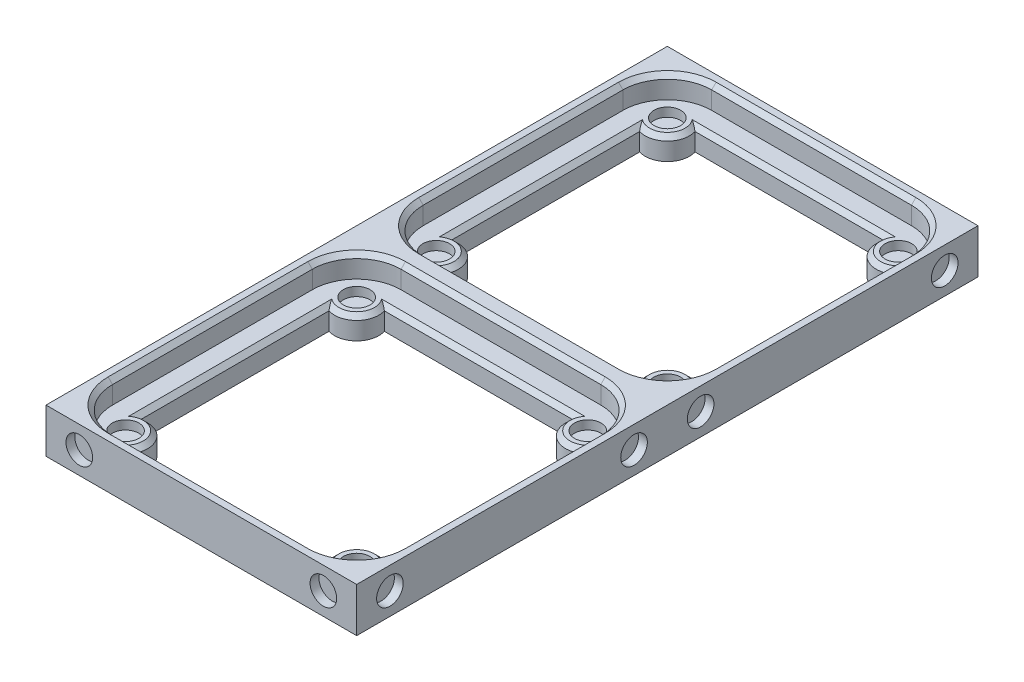
SolidWorks part; units mm, degrees
ref_plane "Front Plane" through (0, 0, 0) normal (0, 0, 1) x (1, 0, 0)
ref_plane "Top Plane" through (0, 0, 0) normal (0, 1, 0) x (1, 0, 0)
ref_plane "Right Plane" through (0, 0, 0) normal (1, 0, 0) x (0, 0, -1)
sketch "Sketch1" plane through (0, 0, 0) normal (0, 1, 0) x (1, 0, 0)
  line L1 (0, 0) -> (70, 0)
  line L2 (0, 0) -> (0, 70)
  line L3 (0, 70) -> (70, 70)
  line L4 (70, 0) -> (70, 70)
  dimension "D1" = 70
  dimension "D2" = 70
extrude "Boss-Extrude2" add sketch "Sketch1" along normal blind 7
sketch "Sketch3" plane through (0, 7, 0) normal (0, 1, 0) x (1, 0, 0)
  line L8 (2.5, 67.5) -> (2.5, 2.5)
  line L9 (2.5, 2.5) -> (67.5, 2.5)
  line L10 (67.5, 2.5) -> (67.5, 67.5)
  line L11 (67.5, 67.5) -> (2.5, 67.5)
  line L12 (2.5, 57.5) -> (2.5, 12.5)
  line L13 (12.5, 2.5) -> (57.5, 2.5)
  line L14 (67.5, 12.5) -> (67.5, 57.5)
  line L15 (57.5, 67.5) -> (12.5, 67.5)
  arc A0 (2.5, 12.5) -> (12.5, 2.5) centre (12.5, 12.5) ccw
  arc A1 (57.5, 2.5) -> (67.5, 12.5) centre (57.5, 12.5) ccw
  arc A2 (67.5, 57.5) -> (57.5, 67.5) centre (57.5, 57.5) ccw
  arc A3 (2.5, 57.5) -> (12.5, 67.5) centre (12.5, 57.5) cw
  dimension "D2" = 10
  dimension "D1" = 2.5
extrude "Cut-Extrude1" cut sketch "Sketch3" against normal blind 5
sketch "Sketch9" plane through (0, 0, 0) normal (0, -1, 0) x (1, 0, 0)
  line L1 (0, -70) -> (70, -70)
  line L2 (0, -70) -> (0, 0)
  line L3 (0, 0) -> (70, 0)
  line L4 (70, -70) -> (70, 0)
extrude "Boss-Extrude3" add sketch "Sketch9" along normal blind 5
sketch "Sketch20" plane through (0, 2, 0) normal (0, 1, 0) x (1, 0, 0)
  line L0 (35, 35) -> (8.9645, 61.0355) construction
  line L19 (12.5, 7.5) -> (57.5, 7.5)
  line L20 (62.5, 12.5) -> (62.5, 57.5)
  line L21 (57.5, 62.5) -> (12.5, 62.5)
  line L22 (7.5, 57.5) -> (7.5, 12.5)
  line L23 (13.7452, 7.5) -> (56.2548, 7.5)
  line L24 (62.5, 13.7452) -> (62.5, 56.2548)
  line L25 (56.2548, 62.5) -> (13.7452, 62.5)
  line L26 (7.5, 56.2548) -> (7.5, 13.7452)
  arc A0 (56.2548, 62.5) -> (62.5, 56.2548) centre (61.0355, 61.0355) ccw
  arc A1 (62.5, 13.7452) -> (56.2548, 7.5) centre (61.0355, 8.9645) ccw
  arc A2 (13.7452, 7.5) -> (7.5, 13.7452) centre (8.9645, 8.9645) ccw
  circle A4 centre (8.9645, 61.0355) radius 3
  circle A5 centre (8.9645, 8.9645) radius 3
  circle A6 centre (61.0355, 8.9645) radius 3
  circle A7 centre (61.0355, 61.0355) radius 3
  arc A21 (7.5, 56.2548) -> (13.7452, 62.5) centre (8.9645, 61.0355) ccw
  arc A24 (7.5, 12.5) -> (12.5, 7.5) centre (12.5, 12.5) ccw
  arc A25 (57.5, 7.5) -> (62.5, 12.5) centre (57.5, 12.5) ccw
  arc A26 (62.5, 57.5) -> (57.5, 62.5) centre (57.5, 57.5) ccw
  arc A27 (12.5, 62.5) -> (7.5, 57.5) centre (12.5, 57.5) ccw
  point P8 (35, 35)
  dimension "D2" = 6
  dimension "D3" = 4
  dimension "D4" = 36.8198
  dimension "D1" = 5
extrude "Cut-Extrude11" cut sketch "Sketch20" against normal through all contours L23 A1 L24 A0 L25 A21 L26 A2
sketch "Sketch21" plane through (0, 2, 0) normal (0, 1, 0) x (1, 0, 0)
  circle A0 centre (8.9645, 61.0355) radius 3
  circle A1 centre (61.0355, 61.0355) radius 3
  circle A2 centre (61.0355, 8.9645) radius 3
  circle A3 centre (8.9645, 8.9645) radius 3
extrude "Cut-Extrude12" cut sketch "Sketch21" against normal blind 2 contours A0 | A1 | A2 | A3
chamfer "Chamfer3" distance 1 angle 45 16 edges at (35, 7, -2.5) (64.5711, 7, -5.4289) (5.4289, 7, -5.4289) (67.5, 7, -35) (2.5, 7, -35) (64.5711, 7, -64.5711) (5.4289, 7, -64.5711) (35, 7, -67.5) (12.5, 2, -12.5) (35, 2, -7.5) (57.5, 2, -12.5) (62.5, 2, -35) (57.5, 2, -57.5) (7.5, 2, -35) (12.5, 2, -57.5) (35, 2, -62.5)
sketch "Sketch22" plane through (0, -5, 0) normal (0, -1, 0) x (1, 0, 0)
  line L0 (7.5, -13.7452) -> (7.5, -56.2548)
  line L1 (0, 0) -> (70, 0)
  line L2 (0, 0) -> (0, -70)
  line L3 (0, -70) -> (70, -70)
  line L4 (70, 0) -> (70, -70)
  line L6 (13.7452, -62.5) -> (56.2548, -62.5)
  line L8 (62.5, -56.2548) -> (62.5, -13.7452)
  line L10 (56.2548, -7.5) -> (13.7452, -7.5)
  arc A0 (7.5, -13.7452) -> (13.7452, -7.5) centre (8.9645, -8.9645) ccw
  arc A1 (56.2548, -7.5) -> (62.5, -13.7452) centre (61.0355, -8.9645) ccw
  arc A2 (62.5, -56.2548) -> (56.2548, -62.5) centre (61.0355, -61.0355) ccw
  arc A3 (13.7452, -62.5) -> (7.5, -56.2548) centre (8.9645, -61.0355) ccw
extrude "Cut-Extrude13" cut sketch "Sketch22" against normal blind 2
ref_plane "Plane2" through (0, 0, -35) normal (0, 0, 1) x (1, 0, 0)
ref_plane "Plane3" through (35, 0, 0) normal (-1, 0, 0) x (0, 0, 1)
sketch "Sketch27" plane through (0, 0, 0) normal (-1, 0, 0) x (0, 0, 1)
  line L0 (-70, -3) -> (-70, 7)
  line L1 (-70, 7) -> (-70, 2)
  line L2 (-70, 2) -> (-62.5, 2)
  line L3 (-35, -5.5) -> (-35, 5.5) construction
  circle A0 centre (-62.5, 2) radius 3
  circle A1 centre (-7.5, 2) radius 3
extrude "Cut-Extrude27" cut sketch "Sketch27" against normal blind 2
sketch "Sketch28" plane through (0, 0, 0) normal (0, 0, 1) x (1, 0, 0)
  line L0 (0, -3) -> (0, 7)
  line L1 (0, 7) -> (0, 2)
  line L2 (0, 2) -> (7.5, 2)
  line L3 (35, 5.5) -> (35, -5.5) construction
  circle A0 centre (7.5, 2) radius 3
  circle A1 centre (62.5, 2) radius 3
extrude "Cut-Extrude28" cut sketch "Sketch28" against normal blind 2
mirror "Mirror2" about plane through (0, 7, -70) normal (0, 0, 1) of bodies 126
mirror "Mirror7" about plane through (35, 0, 0) normal (-1, 0, 0) of "Cut-Extrude27"
ref_plane "Plane6" through (0, 0, -70) normal (0, 0, 1) x (1, 0, 0)
mirror "Mirror8" about plane through (0, 0, -70) normal (0, 0, 1) of "Mirror7"
